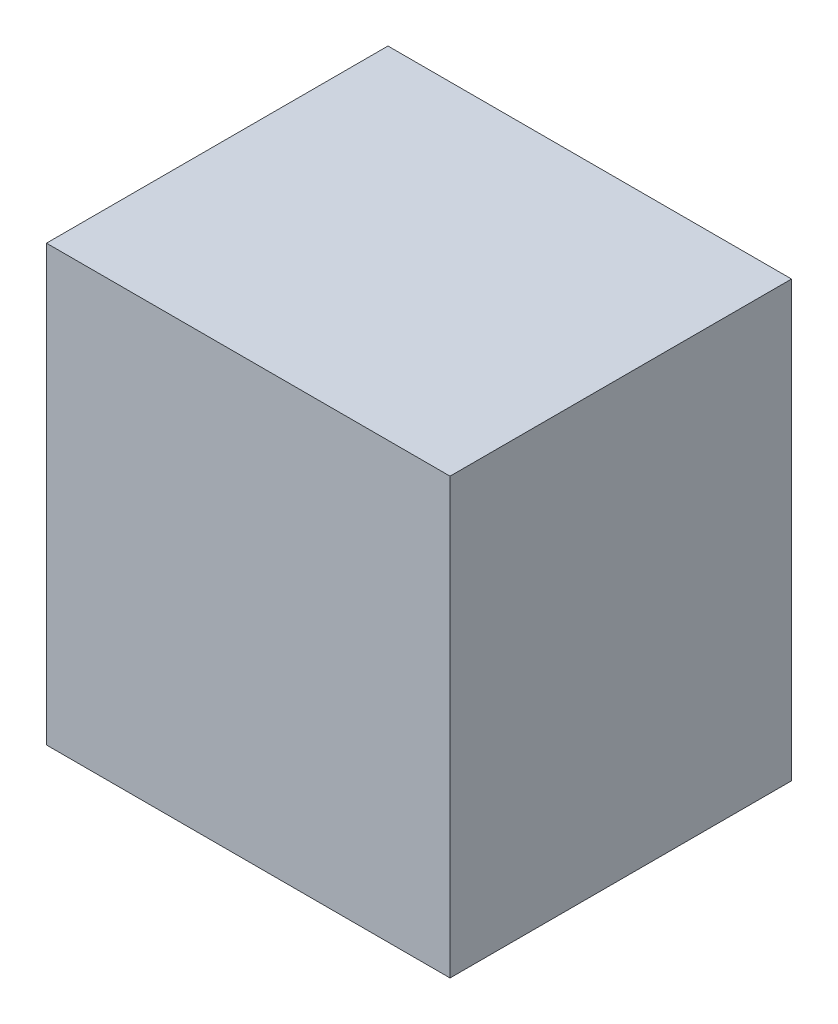
SolidWorks part; units mm, degrees
ref_plane "Front Plane" through (0, 0, 0) normal (0, 0, 1) x (1, 0, 0)
ref_plane "Top Plane" through (0, 0, 0) normal (0, 1, 0) x (1, 0, 0)
ref_plane "Right Plane" through (0, 0, 0) normal (1, 0, 0) x (0, 0, -1)
ref_plane "Plane1" through (0, 0, 0) normal (0, 0, -1) x (-1, 0, 0)
sketch "Sketch1" plane through (0, 0, 0) normal (0, 0, -1) x (-1, 0, 0)
  line L0 (162.5, -175) -> (162.5, 175)
  line L1 (162.5, 175) -> (-162.5, 175)
  line L2 (-162.5, 175) -> (-162.5, -175)
  line L3 (-162.5, -175) -> (162.5, -175)
extrude "Boss-Extrude1" add sketch "Sketch1" against normal blind 275
